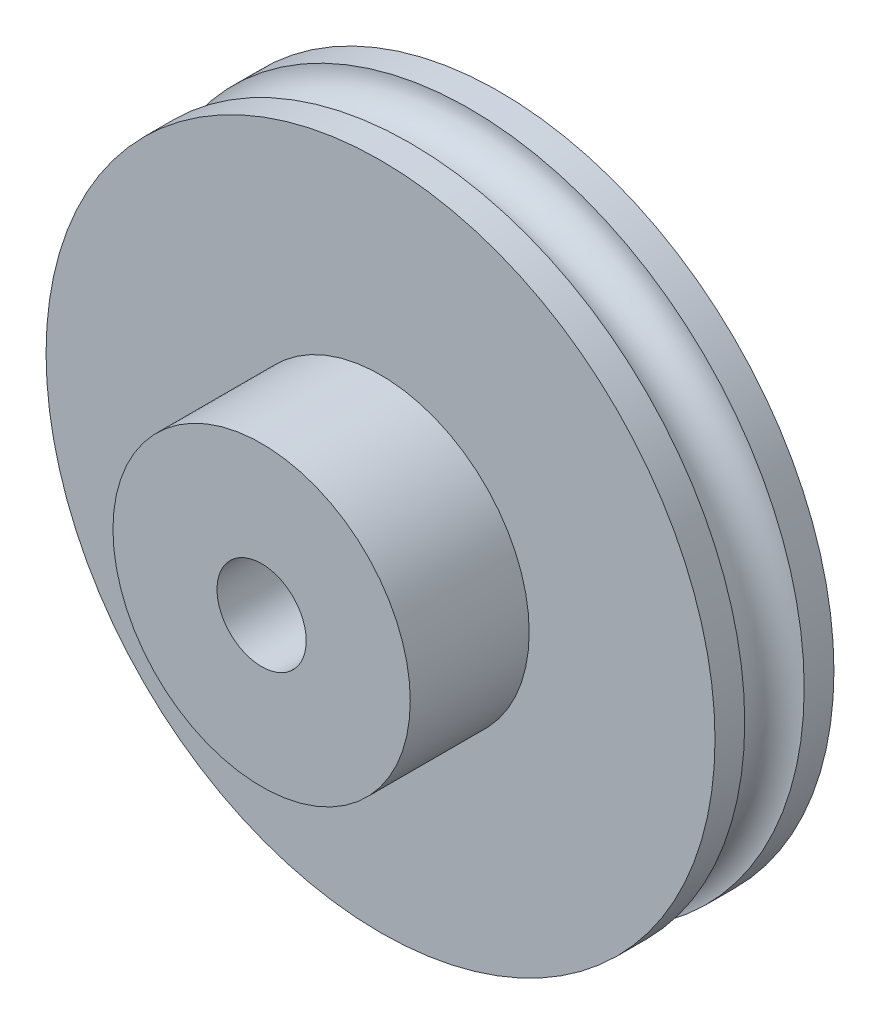
SolidWorks part; units mm, degrees
ref_plane "前视基准面" through (0, 0, 0) normal (0, 0, 1) x (1, 0, 0)
ref_plane "上视基准面" through (0, 0, 0) normal (0, 1, 0) x (1, 0, 0)
ref_plane "右视基准面" through (0, 0, 0) normal (1, 0, 0) x (0, 0, -1)
other "Configuration Table"
sketch "草图1" plane through (0, 0, 0) normal (0, 0, 1) x (1, 0, 0)
  circle A0 centre (0, 0) radius 22.5
  dimension "D1" = 45
extrude "凸台-拉伸1" add sketch "草图1" along normal blind 8
sketch "草图2" plane through (0, 0, 0) normal (0, 1, 0) x (1, 0, 0)
  line L0 (-22.5, 0) -> (-22.5, -8) construction
  circle A0 centre (-22.5, -4) radius 2
  dimension "D1" = 4
revolve "切除-旋转1" cut sketch "草图2" angle 360 about axis through (0, 0, 8) along (0, 0, -1)
sketch "草图3" plane through (0, 0, 8) normal (0, 0, 1) x (1, 0, 0)
  circle A1 centre (0, 0) radius 10
  dimension "D1" = 20
extrude "凸台-拉伸2" add sketch "草图3" along normal blind 8
sketch "草图4" plane through (0, 0, 16) normal (0, 0, 1) x (1, 0, 0)
  circle A0 centre (0, 0) radius 3
  dimension "D1" = 6
extrude "切除-拉伸1" cut sketch "草图4" against normal through all
